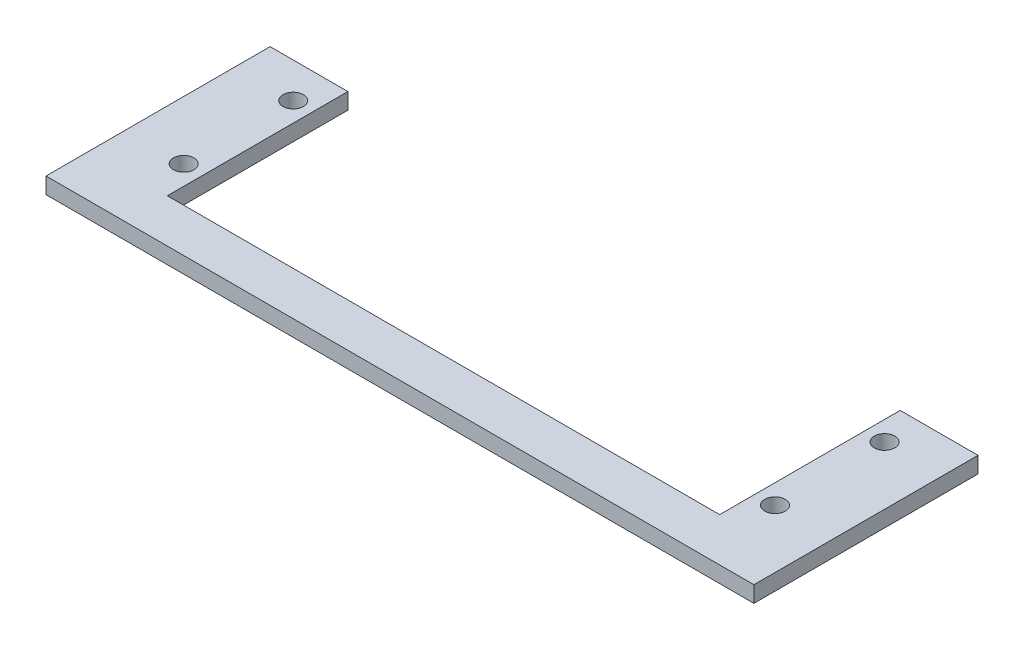
SolidWorks part; units mm, degrees
ref_plane "Front Plane" through (0, 0, 0) normal (0, 0, 1) x (1, 0, 0)
ref_plane "Top Plane" through (0, 0, 0) normal (0, 1, 0) x (1, 0, 0)
ref_plane "Right Plane" through (0, 0, 0) normal (1, 0, 0) x (0, 0, -1)
sketch "Sketch2" plane through (0, 0, 0) normal (0, 1, 0) x (1, 0, 0)
  line L0 (44.365, 0) -> (-44.365, 0) construction
  line L1 (-44.365, 0) -> (-44.365, -29)
  line L2 (-44.365, -29) -> (44.365, -29)
  line L3 (44.365, -29) -> (44.365, 0)
  line L4 (-44.365, 0) -> (-56.865, 0)
  line L5 (-56.865, 0) -> (-56.865, -36)
  line L6 (-56.865, -36) -> (56.865, -36)
  line L7 (56.865, -36) -> (56.865, 0)
  line L8 (56.865, 0) -> (44.365, 0)
  line L10 (47.5, -23.25) -> (-47.5, -23.25) construction
  line L11 (47.5, -23.25) -> (47.5, -5.65) construction
  line L12 (47.5, -5.65) -> (-47.5, -5.65) construction
  line L13 (-47.5, -23.25) -> (-47.5, -5.65) construction
  line L14 (47.5, -23.25) -> (-47.5, -5.65) construction
  line L15 (47.5, -5.65) -> (-47.5, -23.25) construction
  circle A0 centre (-47.5, -5.65) radius 1.65
  circle A1 centre (47.5, -5.65) radius 1.65
  circle A2 centre (-47.5, -23.25) radius 1.65
  circle A3 centre (47.5, -23.25) radius 1.65
  point P4 (0, 0)
  point P15 (0, -14.45)
  dimension "D6" = 3.3
  dimension "D7" = 4
  dimension "D8" = 14.3
  dimension "D1" = 88.73
  dimension "D2" = 29
  dimension "D3" = 12.5
  dimension "D4" = 7
  dimension "D5" = 95
extrude "Boss-Extrude1" add sketch "Sketch2" along normal blind 2.6
